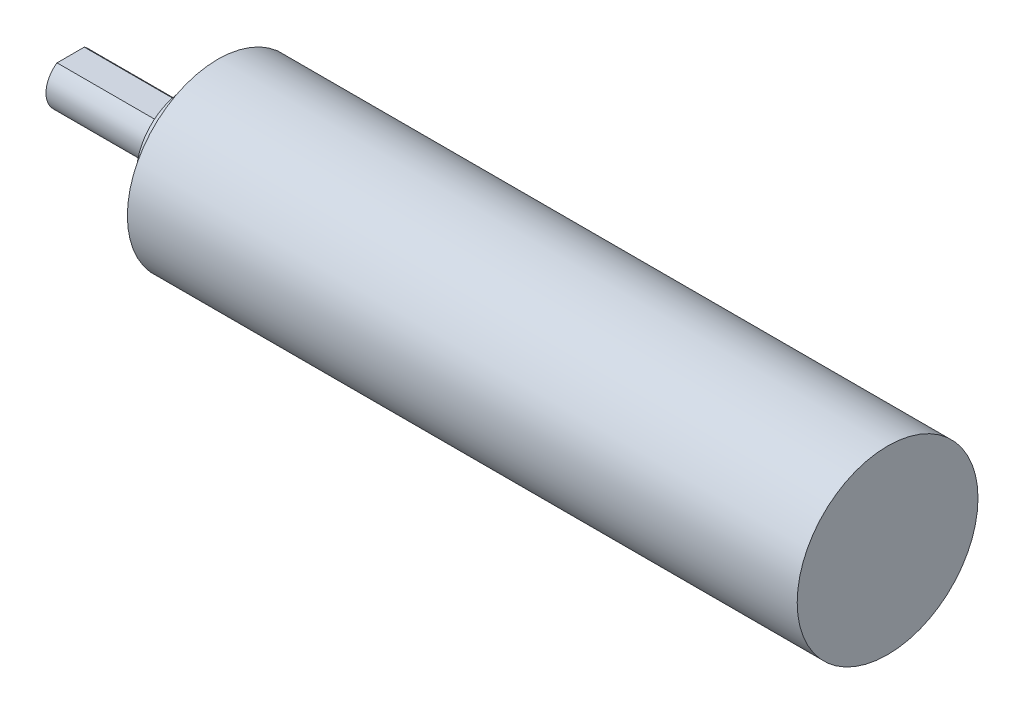
SolidWorks part; units mm, degrees
ref_plane "Front Plane" through (0, 0, 0) normal (0, 0, 1) x (1, 0, 0)
ref_plane "Top Plane" through (0, 0, 0) normal (0, 1, 0) x (1, 0, 0)
ref_plane "Right Plane" through (0, 0, 0) normal (1, 0, 0) x (0, 0, -1)
sketch "Sketch1" plane through (0, 0, 0) normal (0, 0, 1) x (1, 0, 0)
  line L0 (0, 0) -> (23757.6581, 0) construction
  line L1 (0, 0) -> (0, 3)
  line L2 (0, 3) -> (14, 3)
  line L3 (14, 3) -> (14, 6)
  line L4 (14, 6) -> (17.9, 6)
  line L5 (17.9, 6) -> (17.9, 11)
  line L6 (17.9, 11) -> (99.4, 11)
  line L7 (99.4, 11) -> (99.4, 0)
  line L8 (0, 0) -> (99.4, 0)
  dimension "D1" = 12
  dimension "D2" = 6
  dimension "D3" = 22
  dimension "D4" = 3.9
  dimension "D5" = 14
  dimension "D6" = 81.5
revolve "Revolve1" add sketch "Sketch1" angle 360 about L0
hole_wizard "M3x0.5 Tapped Hole1" positions "Sketch2" profile "Sketch3" tap size "M3x0.5" standard "ANSI Metric"
sketch "Sketch2" plane through (17.9, 0, 0) normal (-1, 0, 0) x (0, 0, 1)
  circle A0 centre (0, 0) radius 9
  point P7 (0, 9)
  point P9 (9, 0)
  point P11 (0, -9)
  point P13 (-9, 0)
  dimension "D1" = 18
sketch "Sketch3" plane through (17.9, 0, -9) normal (0, 1, 0) x (0, 0, 1)
  line L0 (0, 0) -> (0, 8.2511)
  line L1 (0, 8.2511) -> (1.25, 7.5)
  line L2 (1.25, 7.5) -> (1.25, 0)
  line L5 (1.25, 0) -> (0, 0)
  line L10 (0, 8.2511) -> (-1.25, 7.5) construction
  line L11 (0, -6.35) -> (0, 107.95) construction
  dimension "Tap Drill Dia." = 2.5
  dimension "Tap Drill Depth" = 7.5
  dimension "Drill Angle" = 118
cosmetic thread "Hole Thread1" parameters "D1"=6, "D2"=3
cosmetic thread "Hole Thread2" parameters "D1"=6, "D2"=3
cosmetic thread "Hole Thread3" parameters "D1"=6, "D2"=3
cosmetic thread "Hole Thread4" parameters "D1"=6, "D2"=3
sketch "Sketch4" plane through (0, 0, 0) normal (-1, 0, 0) x (0, 0, 1)
  line L0 (-1.6583, 2.5) -> (1.6583, 2.5)
  circle A1 centre (0, 0) radius 3
  arc A2 (1.6583, 2.5) -> (-1.6583, 2.5) centre (0, 0) ccw
  dimension "D2" = 5.5
  dimension "D1" = 0
extrude "Cut-Extrude1" cut sketch "Sketch4" against normal blind 14
